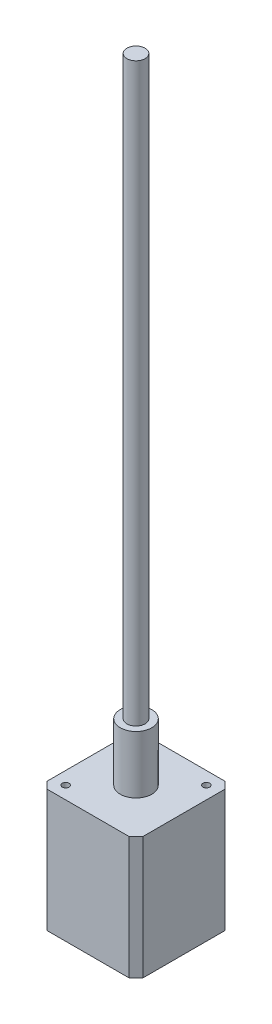
SolidWorks part; units mm, degrees
ref_plane "Front Plane" through (0, 0, 0) normal (0, 0, 1) x (1, 0, 0)
ref_plane "Top Plane" through (0, 0, 0) normal (0, 1, 0) x (1, 0, 0)
ref_plane "Right Plane" through (0, 0, 0) normal (1, 0, 0) x (0, 0, -1)
sketch "Sketch1" plane through (0, 0, 0) normal (0, 1, 0) x (1, 0, 0)
  line L1 (0, 0) -> (42.25, 0)
  line L2 (0, 0) -> (0, 42.25)
  line L3 (0, 42.25) -> (42.25, 42.25)
  line L4 (42.25, 0) -> (42.25, 42.25)
  dimension "D1" = 42.25
extrude "Boss-Extrude1" add sketch "Sketch1" along normal blind 54
sketch "Sketch2" plane through (0, 54, 0) normal (0, 1, 0) x (1, 0, 0)
  line L0 (21.125, 42.25) -> (21.125, 21.125) construction
  line L1 (42.25, 42.25) -> (0, 42.25) construction
  line L2 (0, 21.125) -> (21.125, 21.125) construction
  line L3 (0, 42.25) -> (0, 0) construction
  circle A0 centre (36.625, 36.625) radius 1.5
  circle A1 centre (5.625, 5.625) radius 1.5
  circle A2 centre (5.625, 36.625) radius 1.5 construction
  point P6 (0, 0)
  point P7 (0, 0)
  point P16 (0, 0)
  dimension "D1" = 3
  dimension "D2" = 31
  dimension "D3" = 15.5
  dimension "D4" = 31
  dimension "D5" = 15.5
extrude "Cut-Extrude1" cut sketch "Sketch2" against normal blind 3
chamfer "Chamfer1" distance 3 angle 45 4 edges at (0, 27, -42.25) (0, 27, 0) (42.25, 27, 0) (42.25, 27, -42.25)
ref_plane "Plane1" through (21.125, 0, 0) normal (-1, 0, 0) x (0, 0, 1)
sketch "Sketch3" plane through (21.125, 0, 0) normal (-1, 0, 0) x (0, 0, 1)
  line L0 (-21.125, 54) -> (-21.125, 333.4)
  line L1 (-39.25, 54) -> (-3, 54) construction
  line L2 (-25.125, 79.4) -> (-28.075, 79.4)
  line L3 (-28.075, 79.4) -> (-28.075, 54)
  line L4 (-28.075, 54) -> (-21.125, 54)
  line L5 (-21.125, 333.4) -> (-25.125, 333.4)
  line L6 (-25.125, 333.4) -> (-25.125, 79.4)
  point P6 (0, 0)
  dimension "D1" = 279.4
  dimension "D2" = 6.95
  dimension "D3" = 25.4
  dimension "D4" = 4
revolve "Revolve1" add sketch "Sketch3" angle 360 about L0
